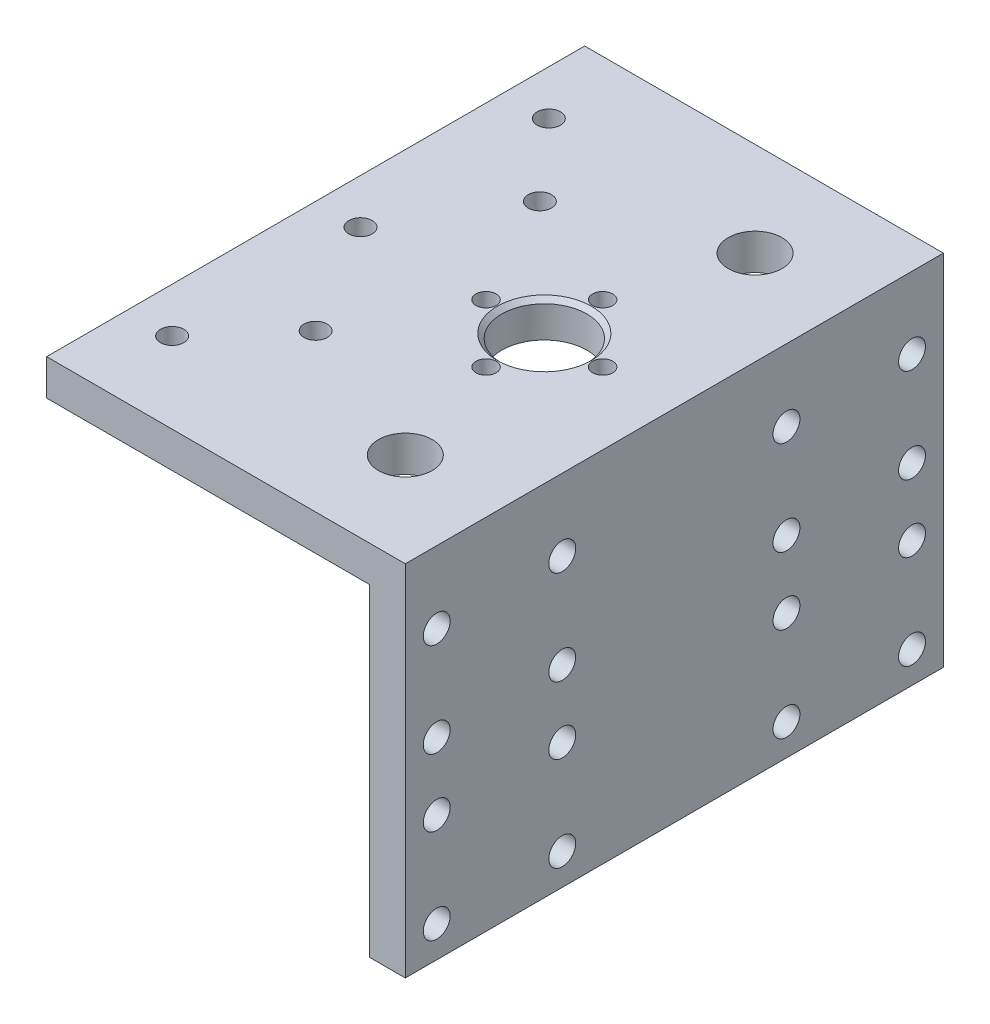
SolidWorks part; units mm, degrees
material "Lega 1060"
ref_plane "Piano frontale" through (0, 0, 0) normal (0, 0, 1) x (1, 0, 0)
ref_plane "Piano superiore" through (0, 0, 0) normal (0, 1, 0) x (1, 0, 0)
ref_plane "Piano destro" through (0, 0, 0) normal (1, 0, 0) x (0, 0, -1)
sketch "Schizzo1" plane through (0, 0, 0) normal (0, 0, 1) x (1, 0, 0)
  line L0 (0, 0) -> (-80, 0)
  line L1 (-80, 0) -> (-80, -8)
  line L2 (-80, -8) -> (-8, -8)
  line L3 (-8, -8) -> (-8, -80)
  line L4 (-8, -80) -> (0, -80)
  line L5 (0, -80) -> (0, 0)
  dimension "D1" = 80
  dimension "D2" = 80
  dimension "D3" = 8
  dimension "D4" = 8
extrude "Estrusione-Estrusione1" add sketch "Schizzo1" along normal blind 120
sketch "Schizzo12" plane through (0, 0, 0) normal (1, 0, 0) x (0, 0, -1)
  line L0 (0, -8) -> (-120, -8) construction
  line L1 (-21, 0) -> (-21, 18.8536) construction
  line L2 (-60, 0) -> (-60, -80) construction
  line L3 (-120, -80) -> (0, -80) construction
  line L5 (0, -80) -> (0, 0) construction
  line L6 (-120, -80) -> (-120, 0) construction
  line L7 (-120, 0) -> (0, 0) construction
  line L10 (-99, -47.4454) -> (-99, 40.839) construction
  line L11 (-128.3276, -73) -> (20.444, -73) construction
  line L13 (-134.9226, -44.5) -> (16.1501, -44.5) construction
  circle A0 centre (-35, -73) radius 3
  circle A1 centre (-7, -73) radius 3
  circle A2 centre (-113, -73) radius 3
  circle A3 centre (-85, -73) radius 3
  circle A4 centre (-85, -52) radius 3
  circle A5 centre (-113, -52) radius 3
  circle A6 centre (-35, -52) radius 3
  circle A7 centre (-7, -52) radius 3
  circle A8 centre (-85, -16) radius 3
  circle A9 centre (-113, -16) radius 3
  circle A10 centre (-35, -37) radius 3
  circle A11 centre (-7, -37) radius 3
  circle A12 centre (-35, -16) radius 3
  circle A13 centre (-7, -16) radius 3
  circle A14 centre (-85, -37) radius 3
  circle A15 centre (-113, -37) radius 3
  dimension "D5" = 6
  dimension "D6" = 43
  dimension "D7" = 64
  dimension "D8" = 25
  dimension "D13" = 35.5
  dimension "D2" = 8
  dimension "D3" = 21
  dimension "D4" = 28
  dimension "D9" = 21
  dimension "D10" = 21
  dimension "D11" = 7
  dimension "D12" = 53
sketch "Schizzo6" plane through (0, 0, 0) normal (0, 1, 0) x (1, 0, 0)
  line L0 (-21, -0.5808) -> (-21, -110.5835) construction
  line L2 (0, 0) -> (-80, 0) construction
  line L3 (-32.5218, -60) -> (-8.0464, -60) construction
  line L6 (0, -120) -> (-80, -120) construction
  circle A0 centre (-21, -21) radius 6
  circle A1 centre (-21, -99) radius 6
  dimension "D2" = 12
  dimension "D1" = 13
  dimension "D3" = 21
  dimension "D4" = 39
extrude "Taglio-Estrusione2" cut sketch "Schizzo6" against normal up to next
sketch "Schizzo7" plane through (0, 0, 0) normal (0, 1, 0) x (1, 0, 0)
  line L0 (-53.636, -60) -> (3.6289, -60) construction
  line L1 (0, -120) -> (-80, -120) construction
  line L2 (0, 0) -> (-80, 0) construction
  line L3 (-21, -21) -> (-21, -99) construction
  circle A0 centre (-29, -60) radius 9.5
  dimension "D1" = 19
  dimension "D2" = 8
extrude "Taglio-Estrusione3" cut sketch "Schizzo7" against normal up to next
hole_wizard "Foro per Vite M4-2" positions "Schizzo9" profile "Schizzo8" hole size "M4" standard "ISO" end condition through all
sketch "Schizzo9" plane through (0, 0, 0) normal (0, 1, 0) x (1, 0, 0)
  line L0 (-18.4657, -60) -> (-16, -60) construction
  line L2 (-29, -57.7684) -> (-29, -66.5063) construction
  circle A2 centre (-29, -60) radius 9.5 construction
  point P0 (-29, -47)
  point P2 (-42, -60)
  point P4 (-29, -73)
  point P8 (-16, -60)
  point P20 (-29, -60)
  dimension "D1" = 26
  dimension "D2" = 13
  dimension "D3" = 13
sketch "Schizzo8" plane through (-29, 0, 47) normal (1, 0, 0) x (0, 0, 1)
  line L0 (0, 0) -> (0, 80)
  line L1 (0, 80) -> (2.25, 80)
  line L2 (2.25, 80) -> (2.25, 0)
  line L5 (2.25, 0) -> (0, 0)
  line L11 (0, -6.35) -> (0, 107.95) construction
  dimension "Thru Hole Dia." = 4.5
  dimension "Thru Hole Depth" = 80
extrude "Taglio-Estrusione4" cut sketch "Schizzo12" against normal blind 10
sketch "Schizzo14" plane through (0, 0, 0) normal (0, 1, 0) x (1, 0, 0)
  line L0 (-70, 0) -> (-70, -120) construction
  line L1 (0, 0) -> (-80, 0) construction
  line L2 (0, -120) -> (-80, -120) construction
  line L3 (-80, -120) -> (-80, 0) construction
  line L4 (-55, 0) -> (-55, -120) construction
  line L5 (-21, -99) -> (-80, -99) construction
  line L6 (-80, -60) -> (0, -60) construction
  line L7 (0, -120) -> (0, 0) construction
  line L8 (-21, -21) -> (-80, -21) construction
  circle A0 centre (-70, -18) radius 2.6
  circle A1 centre (-70, -60) radius 2.6
  circle A2 centre (-70, -102) radius 2.6
  circle A3 centre (-55, -35) radius 2.6
  circle A4 centre (-55, -85) radius 2.6
  dimension "D3" = 5.2
  dimension "D4" = 5.2
  dimension "D5" = 5.2
  dimension "D6" = 5.2
  dimension "D7" = 5.2
  dimension "D1" = 10
  dimension "D2" = 25
  dimension "D8" = 35
  dimension "D9" = 35
  dimension "D10" = 25
  dimension "D11" = 42
  dimension "D12" = 15
extrude "Taglio-Estrusione5" cut sketch "Schizzo14" against normal blind 10
chamfer "Smusso2" distance 1 angle 45 1 edges at (-38.5, 0, 60)
